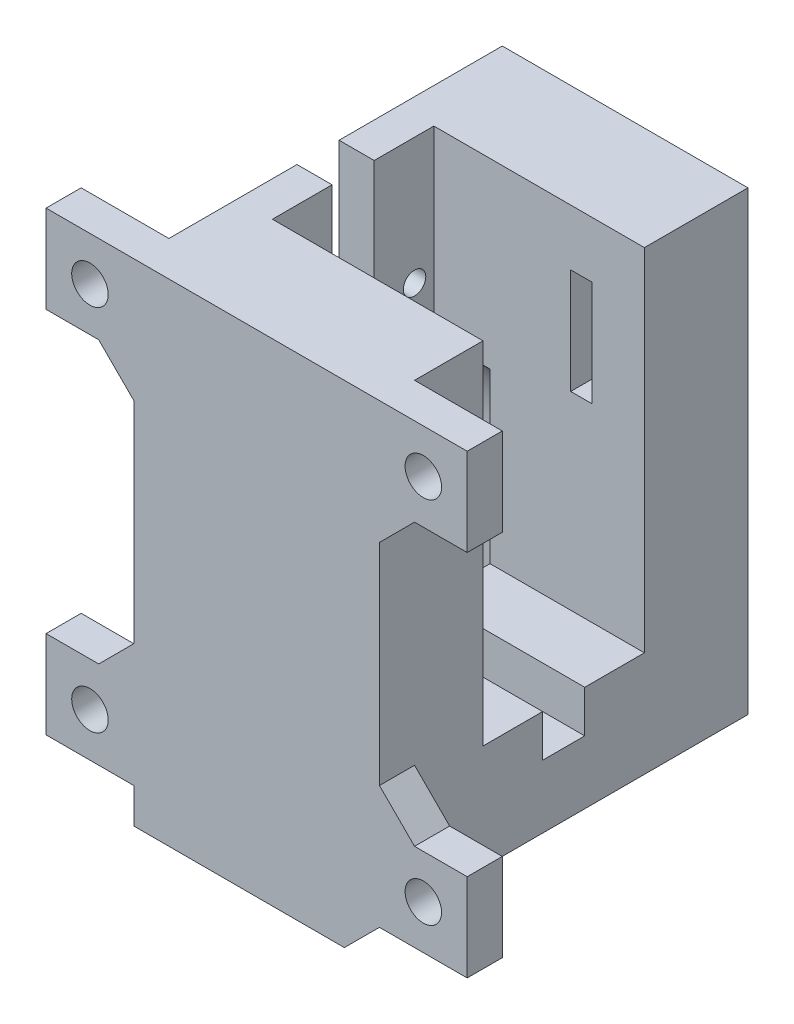
SolidWorks part; units mm, degrees
ref_plane "Front Plane" through (0, 0, 0) normal (0, 0, 1) x (1, 0, 0)
ref_plane "Top Plane" through (0, 0, 0) normal (0, 1, 0) x (1, 0, 0)
ref_plane "Right Plane" through (0, 0, 0) normal (1, 0, 0) x (0, 0, -1)
sketch "Sketch1" plane through (0, 0, 0) normal (0, 0, 1) x (1, 0, 0)
  line L1 (0, 0) -> (40, 0)
  line L2 (0, 0) -> (0, 65)
  line L3 (0, 65) -> (40, 65)
  line L4 (40, 0) -> (40, 65)
  dimension "D1" = 65
  dimension "D2" = 40
extrude "Boss-Extrude1" add sketch "Sketch1" along normal blind 42.5 and the other way blind 15
sketch "Sketch3" plane through (40, 0, 0) normal (1, 0, 0) x (0, 0, -1)
  line L0 (15, 15) -> (0, 15)
  line L1 (15, 0) -> (15, 65) construction
  line L2 (0, 65) -> (0, 15)
  line L3 (15, 65) -> (-42.5, 65) construction
  line L4 (15, 0) -> (-42.5, 0) construction
  line L5 (-22.5, 65) -> (-22.5, 15)
  line L6 (-22.5, 15) -> (0, 15)
  line L7 (-22.5, 65) -> (0, 65)
  line M4 (15, 65) -> (-42.5, 65)
  dimension "D1" = 15
  dimension "D2" = 15
  dimension "D3" = 22.5
extrude "Cut-Extrude2" cut sketch "Sketch3" against normal blind 30 contours L5 L6 L2 M4
sketch "Sketch4" plane through (10, 0, 0) normal (1, 0, 0) x (0, 0, -1)
  line L0 (-11.25, 15) -> (-11.25, 26.5) construction
  line L1 (-22.5, 15) -> (0, 15) construction
  circle A0 centre (-11.25, 26.5) radius 4.5
  dimension "D2" = 9
  dimension "D1" = 11.5
extrude "Cut-Extrude3" cut sketch "Sketch4" against normal blind 10
sketch "Sketch5" plane through (0, 0, 0) normal (0, -1, 0) x (1, 0, 0)
  line L0 (40, 17.5) -> (70, 17.5)
  line L1 (70, 17.5) -> (70, 42.5)
  line L2 (70, 42.5) -> (40, 42.5)
  line L3 (40, 42.5) -> (40, 17.5)
  line L6 (63.817, 25.1893) -> (35.817, 25.1893) construction
  line L8 (40, -15) -> (40, 42.5) construction
  circle A0 centre (63.817, 25.1893) radius 3 construction
  circle A1 centre (35.817, 25.1893) radius 3 construction
  dimension "D1" = 28
  dimension "D2" = 30
  dimension "D3" = 25
sketch "Sketch6" plane through (0, 0, 42.5) normal (0, 0, 1) x (1, 0, 0)
  line L0 (40, 65) -> (40, 0)
  line L1 (40, 0) -> (0, 0)
  line L2 (0, 0) -> (0, 65)
  line L3 (0, 65) -> (40, 65)
extrude "Cut-Extrude4" cut sketch "Sketch6" against normal blind 5
sketch "Sketch7" plane through (0, 0, 0) normal (0, -1, 0) x (1, 0, 0)
  line L0 (40, 42.5) -> (40, 17.5) construction
  line L1 (0, 37.5) -> (40, 37.5) construction
  line L2 (28, 25.5) -> (28, -3) construction
  line L3 (40, -15) -> (40, 11.25) construction
  line L4 (40, -15) -> (40, 37.5) construction
  line L5 (40, 11.25) -> (13.6736, 11.25) construction
  circle A0 centre (28, 25.5) radius 3.1
  circle A1 centre (28, -3) radius 3.1
  point P13 (28, 11.25)
  dimension "D1" = 6.2
  dimension "D3" = 12
  dimension "D4" = 6.2
  dimension "D2" = 12
extrude "Cut-Extrude5" cut sketch "Sketch7" against normal blind 10
sketch "Sketch8" plane through (0, 0, 0) normal (-1, 0, 0) x (0, 0, 1)
  line L4 (37.5, 0) -> (37.5, 65)
  line L5 (37.5, 65) -> (-15, 65)
  line L6 (-15, 65) -> (-15, 0)
  line L7 (-15, 0) -> (37.5, 0)
  line L8 (37.5, 0) -> (37.5, 65)
  line L9 (37.5, 65) -> (-15, 65)
  line L10 (-15, 65) -> (-15, 0)
  line L11 (-15, 0) -> (37.5, 0)
  dimension "D1" = 0
extrude "Cut-Extrude6" cut sketch "Sketch8" against normal blind 5
ref_plane "Plane1" through (0, 0, 37.5) normal (0, 0, 1) x (1, 0, 0)
sketch "Sketch9" plane through (0, 0, 37.5) normal (0, 0, 1) x (1, 0, 0)
  line L0 (5, 65) -> (-7.5, 65)
  line L1 (-7.5, 65) -> (-7.5, 52.5)
  line L2 (-7.5, 52.5) -> (5, 52.5)
  line L3 (5, 65) -> (5, 0) construction
  line L4 (22.5, 0) -> (22.5, 65) construction
  line L5 (5, 0) -> (40, 0) construction
  line L6 (40, 65) -> (5, 65) construction
  line L7 (5, 32.5) -> (40, 32.5) construction
  line L8 (40, 0) -> (40, 65) construction
  line L9 (5, 52.5) -> (5, 65)
  line L10 (40, 52.5) -> (40, 65)
  line L11 (40, 65) -> (52.5, 65)
  line L12 (52.5, 65) -> (52.5, 52.5)
  line L13 (52.5, 52.5) -> (40, 52.5)
  line L14 (40, 0) -> (52.5, 0)
  line L15 (52.5, 0) -> (52.5, 12.5)
  line L16 (52.5, 12.5) -> (40, 12.5)
  line L17 (40, 12.5) -> (40, 0)
  line L18 (5, 12.5) -> (5, 0)
  line L19 (5, 0) -> (-7.5, 0)
  line L20 (-7.5, 0) -> (-7.5, 12.5)
  line L21 (-7.5, 12.5) -> (5, 12.5)
  circle A0 centre (-1.25, 58.75) radius 2.6
  circle A1 centre (46.25, 58.75) radius 2.6
  circle A2 centre (46.25, 6.25) radius 2.6
  circle A3 centre (-1.25, 6.25) radius 2.6
  dimension "D1" = 5.2
extrude "Boss-Extrude2" add sketch "Sketch9" against normal blind 5
sketch "Sketch10" plane through (0, 0, 0) normal (0, -1, 0) x (1, 0, 0)
  line L0 (40, 32.5) -> (40, 37.5)
  line L2 (5, -15) -> (5, 32.5) construction
  line L3 (5, -15) -> (5, 37.5)
  line L8 (52.5, 37.5) -> (-7.5, 37.5)
  line L9 (-7.5, 37.5) -> (-7.5, 32.5)
  line L10 (-7.5, 32.5) -> (5, 32.5)
  line L11 (5, 32.5) -> (5, -15)
  line L12 (5, -15) -> (40, -15)
  line L13 (40, -15) -> (40, 32.5)
  line L14 (40, 32.5) -> (52.5, 32.5)
  line L15 (52.5, 32.5) -> (52.5, 37.5)
  line L16 (40, 37.5) -> (5, 37.5)
  line L20 (5, -15) -> (40, -15)
  line L21 (40, -15) -> (40, 32.5)
  circle A0 centre (28, 25.5) radius 3.1 construction
  circle A1 centre (28, -3) radius 3.1 construction
  circle A2 centre (28, 25.5) radius 3.1
  circle A3 centre (28, -3) radius 3.1
  dimension "D1" = 0
extrude "Boss-Extrude3" add sketch "Sketch10" along normal blind 5
sketch "Sketch11" plane through (10, 0, 0) normal (1, 0, 0) x (0, 0, -1)
  circle A0 centre (-2.5, 47) radius 1.6
  circle A1 centre (-20, 47) radius 1.6
  dimension "D1" = 3.2
  dimension "D2" = 3.2
extrude "Cut-Extrude7" cut sketch "Sketch11" against normal through all
ref_plane "Plane2" through (0, 0, 11.25) normal (0, 0, -1) x (-1, 0, 0)
sketch "Sketch12" plane through (0, 0, 11.25) normal (0, 0, -1) x (-1, 0, 0)
  line L0 (-40, 65) -> (-40, 15)
  line L1 (-40, 15) -> (-10, 15)
  line L2 (-10, 15) -> (-10, 65)
  line L3 (-10, 65) -> (-40, 65)
extrude "Cut-Extrude8" cut sketch "Sketch12" against normal blind 11.5 and the other way blind 11.5
sketch "Sketch13" plane through (40, 0, 0) normal (1, 0, 0) x (0, 0, -1)
  line L0 (-11.25, 15) -> (-11.25, 1.5513) construction
  line L1 (-22.75, 15) -> (0.25, 15) construction
  line L2 (-11.25, -55) -> (-11.25, 55) construction
  line L3 (-11.25, 15) -> (-8.25, 15)
  line L4 (-22.75, 15) -> (0.25, 15) construction
  line L5 (-8.25, 15) -> (-8.25, 9)
  line L6 (-8.25, 9) -> (-14.25, 9)
  line L7 (-14.25, 9) -> (-14.25, 15)
  line L8 (-14.25, 15) -> (-11.25, 15)
extrude "Cut-Extrude9" cut sketch "Sketch13" against normal up to surface (30 mm away) up to face at (10, 47, 0.9)
sketch "Sketch14" plane through (0, 65, 0) normal (0, 1, 0) x (1, 0, 0)
  line L0 (10, -11.25) -> (5, -11.25) construction
  line L1 (10, 0.25) -> (10, -22.75) construction
  line L2 (55, -11.25) -> (-55, -11.25) construction
  line L3 (5, -32.5) -> (5, 15) construction
  line L4 (5, -11.25) -> (5, -8.25)
  line L5 (5, -8.25) -> (10, -8.25)
  line L6 (10, -8.25) -> (10, 0.25) construction
  line L7 (10, -8.25) -> (10, -14.25)
  line L8 (10, -8.25) -> (10, -14.25) construction
  line L9 (10, -14.25) -> (5, -14.25)
  line L10 (5, -14.25) -> (5, -11.25)
extrude "Cut-Extrude10" cut sketch "Sketch14" against normal blind 15
sketch "Sketch15" plane through (5, 0, 0) normal (-1, 0, 0) x (0, 0, 1)
  line L0 (-5.75, -5) -> (-5.75, 26.5)
  line L1 (-5.75, -5) -> (28.25, -5)
  line L2 (28.25, -5) -> (28.25, 26.5)
  line L3 (37.5, -5) -> (-15, -5) construction
  circle A0 centre (11.25, 26.5) radius 17
  line M5 (-15, -5) -> (37.5, -5)
  circle M18 centre (11.25, 26.5) radius 4.5
  dimension "D1" = 34
extrude "Cut-Extrude11" cut sketch "Sketch15" against normal blind 13 contours A0 M18 | A0 L0 L2 M5
chamfer "Chamfer1" distance 1 angle 45 3 edges at (5, 10.75, 28.25) (5, 43.5, 11.25) (5, 10.75, -5.75)
sketch "Sketch16" plane through (5, 0, 0) normal (-1, 0, 0) x (0, 0, 1)
  line L0 (-15, 5) -> (-5.75, 5)
  line L1 (-15, 65) -> (-15, -5) construction
  line L2 (-5.75, 26.5) -> (-5.75, -5) construction
  line L3 (-5.75, 5) -> (-5.75, -5)
  line L4 (-5.75, -5) -> (-15, -5)
  line L5 (-15, -5) -> (-15, 5)
extrude "Cut-Extrude12" cut sketch "Sketch16" against normal blind 2
ref_plane "Plane3" through (69.2186, 6.6, 8.1809) normal (0, -1, 0) x (-1, 0, 0)
sketch "Sketch17" plane through (69.2186, 6.6, 8.1809) normal (0, -1, 0) x (-1, 0, 0)
  line L0 (51.2186, 2.2309) -> (82.2186, 2.2309)
  line L1 (51.2186, -9.7691) -> (51.2186, 2.2309)
  line L2 (51.2186, 13.9309) -> (51.2186, -20.0691) construction
  line L3 (82.2186, 2.2309) -> (82.2186, -9.7691)
  line L4 (82.2186, -9.7691) -> (51.2186, -9.7691)
  line L5 (51.2186, 2.2309) -> (51.2186, 7.2309)
  line L6 (51.2186, 2.2309) -> (56.2186, 2.2309)
  line L7 (51.2186, 7.2309) -> (56.2186, 2.2309)
  line L8 (90.9869, -3.7691) -> (95.7879, -3.7691) construction
  line L9 (51.2186, -9.7691) -> (51.2186, -14.5691)
  line L10 (51.2186, -14.5691) -> (56.2186, -9.7691)
  circle A0 centre (56.7211, -3.0691) radius 2.1
  circle A1 centre (76.5411, -3.0691) radius 2.1
  dimension "D2" = 31
  dimension "D3" = 5
  dimension "D4" = 5
extrude "Boss-Extrude4" add sketch "Sketch17" along normal blind 5 contours L7 L5 L0 | L9 L10 L4 | L8 L1 L4 L3 A1 A0 | L1 L8 A0 A1 L3 L0
chamfer "Chamfer2" distance 5 angle 45 1 edges at (40, -5, 11.25)
chamfer "Chamfer3" distance 5 angle 45 2 edges at (40, 52.5, 35) (40, 12.5, 35)
chamfer "Chamfer4" distance 5 angle 45 2 edges at (5, 52.5, 35) (5, 12.5, 35)
sketch "Sketch18" plane through (0, 0, -15) normal (0, 0, -1) x (-1, 0, 0)
  line L0 (-32.5, 57) -> (-29.5, 57)
  line L2 (-29.5, 57) -> (-29.5, 42)
  line L3 (-29.5, 42) -> (-32.5, 42)
  line L4 (-32.5, 42) -> (-32.5, 57)
  line L5 (-40, 65) -> (-5, 65) construction
  dimension "D2" = 8
  dimension "D3" = 15
  dimension "D4" = 3
extrude "Cut-Extrude13" cut sketch "Sketch18" against normal blind 40.75
ref_plane "Plane4" through (17, 0, 0) normal (-1, 0, 0) x (0, 0, 1)
sketch "Sketch20" plane through (17, 0, 0) normal (-1, 0, 0) x (0, 0, 1)
  line L0 (-15, -3.25) -> (-35, -3.2)
  line L1 (-15, 5) -> (-15, -5) construction
  line L2 (-35, -3.2) -> (-35, 6.7)
  line L3 (-35, 6.7) -> (-15, 6.7)
  line L4 (-15, 65) -> (-15, 5) construction
  line L5 (-15, 6.7) -> (-15, -3.25)
  circle A1 centre (-29.75, 3.9) radius 1.2
  circle A2 centre (-20.15, 3.9) radius 1.2
extrude "Boss-Extrude5" add sketch "Sketch20" along normal blind 5
